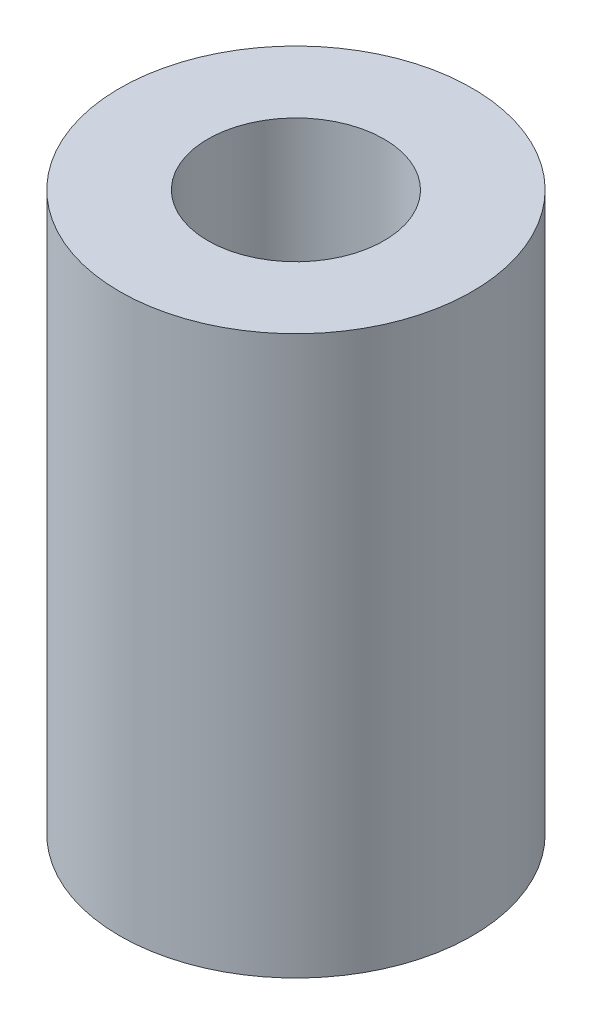
SolidWorks part; units mm, degrees
ref_plane "Front Plane" through (0, 0, 0) normal (0, 0, 1) x (1, 0, 0)
ref_plane "Top Plane" through (0, 0, 0) normal (0, 1, 0) x (1, 0, 0)
ref_plane "Right Plane" through (0, 0, 0) normal (1, 0, 0) x (0, 0, -1)
sketch "Sketch1" plane through (0, 0, 0) normal (0, 1, 0) x (1, 0, 0)
  circle A0 centre (0, 0) radius 3
  circle A1 centre (0, 0) radius 6
  dimension "D1" = 6
  dimension "D2" = 12
extrude "Body" add sketch "Sketch1" along normal blind 19
